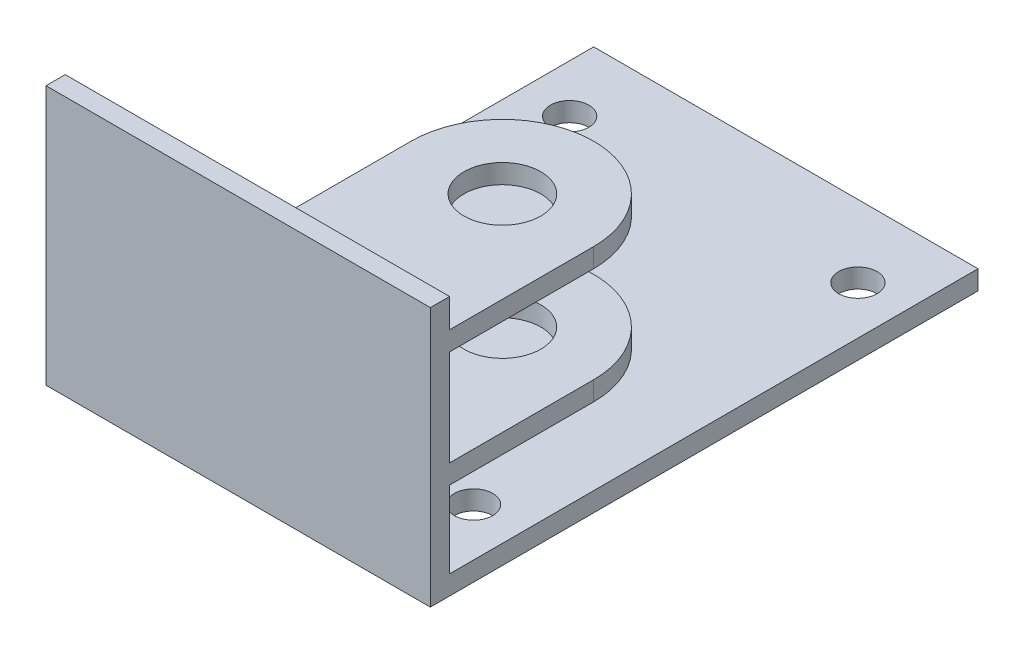
SolidWorks part; units mm, degrees
material "AISI 1045 Acero estirado en frío"
ref_plane "Front" through (0, 0, 0) normal (0, 0, 1) x (1, 0, 0)
ref_plane "Top" through (0, 0, 0) normal (0, 1, 0) x (1, 0, 0)
ref_plane "Right" through (0, 0, 0) normal (1, 0, 0) x (0, 0, -1)
sketch "Croquis2" plane through (0, 0, 0) normal (0, 1, 0) x (1, 0, 0)
  line L1 (20, 55) -> (20, 0) construction
  line L2 (0, 0) -> (40, 0)
  line L3 (0, 0) -> (0, 55)
  line L4 (0, 55) -> (40, 55)
  line L5 (40, 0) -> (40, 55)
  circle A0 centre (5, 47.5) radius 2
  circle A1 centre (35, 47.5) radius 2
  circle A2 centre (35, 7.5) radius 2
  circle A3 centre (5, 7.5) radius 2
  dimension "D2" = 30
  dimension "D3" = 4
  dimension "D4" = 7.5
  dimension "D5" = 5
  dimension "D6" = 7.5
  dimension "D7" = 40
  dimension "D1" = 5
  dimension "5.5" = 55
extrude "Saliente-Extruir1" add sketch "Croquis2" along normal blind 2
sketch "Croquis3" plane through (0, 0, 0) normal (0, 1, 0) x (1, 0, 0)
  line L0 (40, 0) -> (40, 55) construction
  line L1 (0, 0) -> (40, 0)
  line L2 (0, 0) -> (0, -2)
  line L3 (0, -2) -> (40, -2)
  line L4 (40, 0) -> (40, -2)
  dimension "D1" = 2
extrude "Saliente-Extruir2" add sketch "Croquis3" along normal blind 42
ref_plane "Plano1" through (0, 22, 0) normal (0, 1, 0) x (1, 0, 0)
sketch "Croquis4" plane through (0, 22, 0) normal (0, 1, 0) x (1, 0, 0)
  line L1 (40, 15) -> (40, 0)
  line L2 (0, 0) -> (40, 0) construction
  line L3 (40, 0) -> (21, 0)
  line L4 (40, 0) -> (0, 0) construction
  line L5 (21, 0) -> (21, 15)
  circle A0 centre (30.5, 15) radius 4
  arc A1 (40, 15) -> (21, 15) centre (30.5, 15) ccw
  dimension ".8" = 8
  dimension "1.9" = 9.5
  dimension "D2" = 15
extrude "Saliente-Extruir3" add sketch "Croquis4" along normal blind 2
pattern_linear "MatrizL1" count 2 spacing 12 along (0, -1, 0) of "Saliente-Extruir3"
sketch "Croquis5" plane through (0, 0, 0) normal (0, 0, -1) x (-1, 0, 0)
  line L0 (-40, 22) -> (-40, 12) construction
  line L1 (-21, 12) -> (-40, 12)
  line L2 (-21, 12) -> (-21, 22)
  line L3 (-21, 22) -> (-40, 22)
  line L4 (-40, 12) -> (-40, 22)
  line L5 (-21, 22) -> (-40, 22) construction
extrude "Saliente-Extruir4" [suppressed] add sketch "Croquis5" along normal blind 2
sketch "Croquis6" plane through (0, 0, 0) normal (0, 0, -1) x (-1, 0, 0)
  line L0 (-40, 42) -> (-40, 24) construction
  line L1 (0, 42) -> (-40, 42)
  line L2 (0, 42) -> (0, 27)
  line L3 (0, 27) -> (-40, 27)
  line L4 (-40, 42) -> (-40, 27)
  dimension "D1" = 15
extrude "Cortar-Extruir1" cut sketch "Croquis6" against normal blind 10
